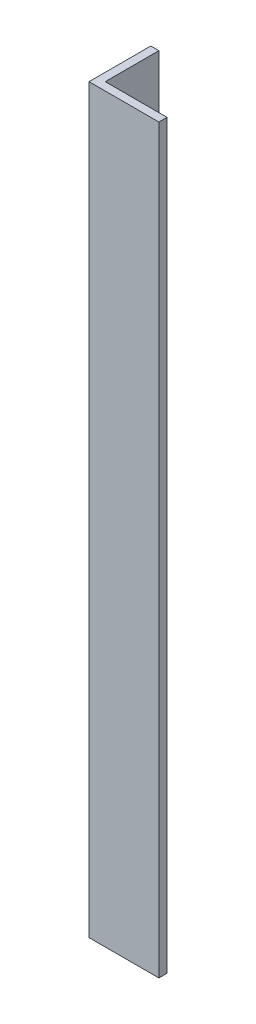
SolidWorks part; units mm, degrees
ref_plane "Front Plane" through (0, 0, 0) normal (0, 0, 1) x (1, 0, 0)
ref_plane "Top Plane" through (0, 0, 0) normal (0, 1, 0) x (1, 0, 0)
ref_plane "Right Plane" through (0, 0, 0) normal (1, 0, 0) x (0, 0, -1)
sketch "Sketch1" plane through (0, 0, 0) normal (0, 1, 0) x (1, 0, 0)
  line L1 (0, 0) -> (-5, 0)
  line L2 (0, 5) -> (0, 38.1)
  line L3 (0, 38.1) -> (-5, 38.1)
  line L4 (-5, 0) -> (-5, 38.1)
  line L5 (0, 0) -> (38.1, 0)
  line L7 (0, 5) -> (38.1, 5)
  line L8 (38.1, 0) -> (38.1, 5)
  dimension "D1" = 38.1
  dimension "D2" = 38.1
  dimension "D3" = 5
  dimension "D4" = 5
  dimension "D5" = 90
extrude "Boss-Extrude1" add sketch "Sketch1" along normal blind 457.2
